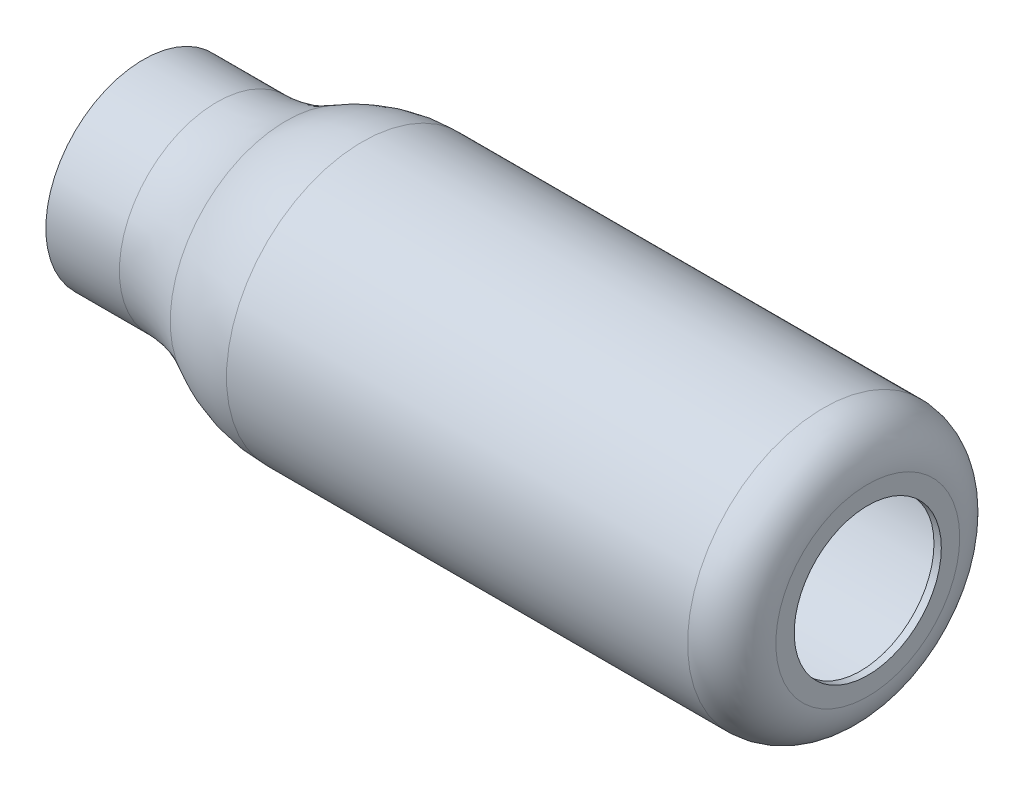
SolidWorks part; units mm, degrees
material "AISI 1020"
ref_plane "Front Plane" through (0, 0, 0) normal (0, 0, 1) x (1, 0, 0)
ref_plane "Top Plane" through (0, 0, 0) normal (0, 1, 0) x (1, 0, 0)
ref_plane "Right Plane" through (0, 0, 0) normal (1, 0, 0) x (0, 0, -1)
sketch "Sketch1" plane through (0, 0, 0) normal (0, 0, 1) x (1, 0, 0)
  line L0 (0, 12.7) -> (0, 15.875)
  line L1 (-6.35, 22.225) -> (-85.9663, 22.225)
  line L2 (-111.125, 15.5575) -> (-123.825, 15.5575)
  line L4 (0, 0) -> (-121.8707, 0) construction
  arc A0 (0, 15.875) -> (-6.35, 22.225) centre (-6.35, 15.875) ccw
  arc A1 (-85.9663, 22.225) -> (-98.5456, 18.8912) centre (-85.9663, -3.175) ccw
  arc A2 (-98.5456, 18.8912) -> (-111.125, 15.5575) centre (-111.125, 40.9575) cw
  dimension "D2" = 123.825
  dimension "D6" = 25.4
  dimension "D1" = 6.35
  dimension "D3" = 44.45
  dimension "D4" = 31.115
  dimension "D5" = 25.4
  dimension "D7" = 12.7
revolve "Revolve-Thin1" add sketch "Sketch1" angle 360 about L4
